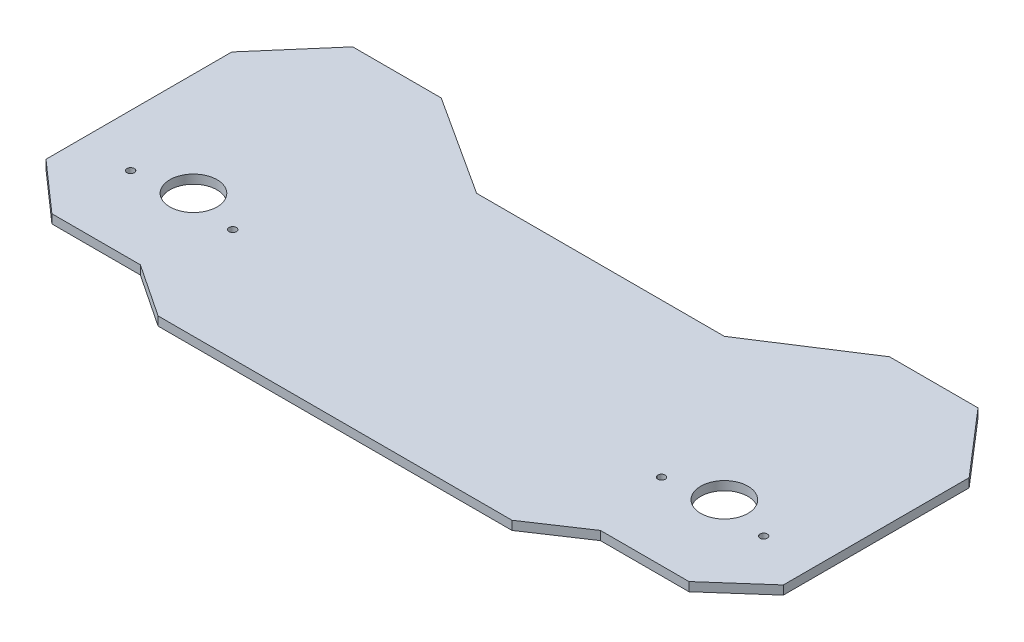
SolidWorks part; units mm, degrees
ref_plane "Front Plane" through (0, 0, 0) normal (0, 0, 1) x (1, 0, 0)
ref_plane "Top Plane" through (0, 0, 0) normal (0, 1, 0) x (1, 0, 0)
ref_plane "Right Plane" through (0, 0, 0) normal (1, 0, 0) x (0, 0, -1)
sketch "Sketch1" plane through (0, 0, 0) normal (0, 1, 0) x (1, 0, 0)
  line L0 (-42, 45) -> (42, 45)
  line L1 (42, 45) -> (76, 67)
  line L2 (76, 67) -> (106, 67)
  line L3 (106, 67) -> (125, 45)
  line L4 (125, 45) -> (125, -18)
  line L5 (125, -18) -> (108, -33)
  line L6 (108, -33) -> (78, -33)
  line L7 (78, -33) -> (60, -45)
  line L8 (60, -45) -> (-60, -45)
  line L9 (-60, -45) -> (-78, -33)
  line L10 (-78, -33) -> (-108, -33)
  line L11 (-108, -33) -> (-125, -18)
  line L12 (-125, -18) -> (-125, 45)
  line L13 (-125, 45) -> (-106, 67)
  line L14 (-106, 67) -> (-76, 67)
  line L15 (-76, 67) -> (-42, 45)
  line L16 (-90, -3) -> (90, -3) construction
  circle A0 centre (-90, -3) radius 8
  circle A1 centre (90, -3) radius 8
  circle A2 centre (-72.7, -7) radius 1.25
  circle A3 centre (-107.3, -7) radius 1.25
  circle A4 centre (72.7, -7) radius 1.25
  circle A5 centre (107.3, -7) radius 1.25
  point P21 (0, 45)
  point P23 (0, -3)
  dimension "D6" = 16
  dimension "D7" = 16
  dimension "D8" = 180
  dimension "D25" = 30
  dimension "D27" = 4
  dimension "D28" = 2.5
  dimension "D29" = 2.5
  dimension "D33" = 17.3
  dimension "D36" = 2.5
  dimension "D37" = 2.5
  dimension "D1" = 90
  dimension "D2" = 45
  dimension "D3" = 250
  dimension "D4" = 112
  dimension "D5" = 0
  dimension "D9" = 30
  dimension "D10" = 17
  dimension "D11" = 17
  dimension "D12" = 30
  dimension "D13" = 120
  dimension "D14" = 0
  dimension "D15" = 125
  dimension "D16" = 84
  dimension "D17" = 0
  dimension "D18" = 30
  dimension "D19" = 30
  dimension "D20" = 34
  dimension "D21" = 34
  dimension "D22" = 63
  dimension "D23" = 63
  dimension "D24" = 12
  dimension "D26" = 4
  dimension "D30" = 17.3
  dimension "D31" = 17.3
  dimension "D32" = 17.3
  dimension "D34" = 4
  dimension "D35" = 4
extrude "Boss-Extrude1" add sketch "Sketch1" along normal blind 3
